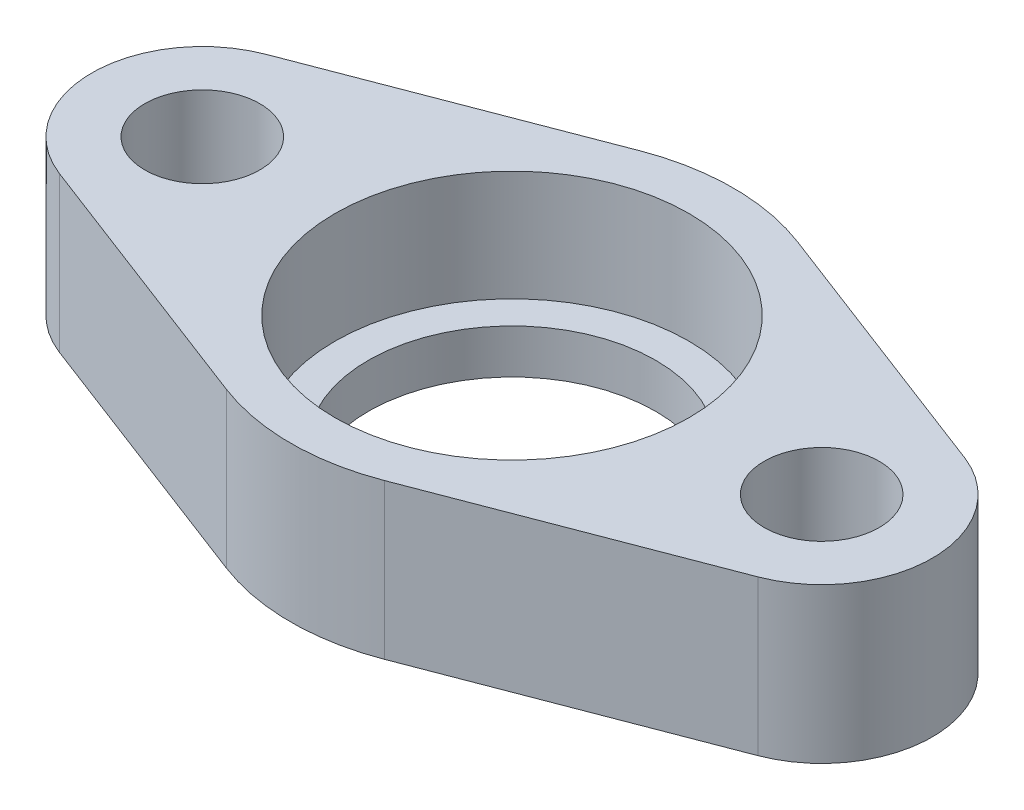
SolidWorks part; units mm, degrees
ref_plane "Front Plane" through (0, 0, 0) normal (0, 0, 1) x (1, 0, 0)
ref_plane "Top Plane" through (0, 0, 0) normal (0, 1, 0) x (1, 0, 0)
ref_plane "Right Plane" through (0, 0, 0) normal (1, 0, 0) x (0, 0, -1)
sketch "Sketch1" plane through (0, 0, 0) normal (0, 1, 0) x (1, 0, 0)
  circle A0 centre (0, 0) radius 4
  circle A1 centre (0, 0) radius 5
  dimension "D1" = 8
  dimension "D2" = 10
extrude "Boss-Extrude1" add sketch "Sketch1" along normal blind 3.5
sketch "Sketch2" plane through (0, 0, 0) normal (0, 1, 0) x (1, 0, 0)
  line L0 (-7.8929, 2.3351) -> (-1.7857, 4.6702)
  line L1 (-9.3607, 0) -> (9.6441, 0) construction
  line L2 (0, 4) -> (0, -5.1211) construction
  line L3 (-7.8929, -2.3351) -> (-1.7857, -4.6702)
  line L4 (7.8929, -2.3351) -> (1.7857, -4.6702)
  line L5 (7.8929, 2.3351) -> (1.7857, 4.6702)
  arc A0 (-7.8929, 2.3351) -> (-7.8929, -2.3351) centre (-7, 0) ccw
  arc A1 (-1.7857, 4.6702) -> (-1.7857, -4.6702) centre (0, 0) ccw
  arc A2 (7.8929, 2.3351) -> (7.8929, -2.3351) centre (7, 0) cw
  arc A3 (1.7857, -4.6702) -> (1.7857, 4.6702) centre (0, 0) ccw
  dimension "D1" = 5
  dimension "D3" = 10
  dimension "D2" = 7
extrude "Boss-Extrude2" add sketch "Sketch2" along normal up to surface (3.5 mm away) up to face at (0, 3.5, 5)
hole_wizard "M2 Clearance Hole1" positions "Sketch4" profile "Sketch3" hole size "M2" standard "ANSI Metric" end condition through all
sketch "Sketch4" plane through (0, 3.5, 0) normal (0, 1, 0) x (1, 0, 0)
  line L0 (0, 1.4124) -> (0, -1.3898) construction
  point P0 (-7, 0)
  point P9 (7, 0)
sketch "Sketch3" plane through (-7, 3.5, 0) normal (1, 0, 0) x (0, 0, 1)
  line L0 (0, 0) -> (0, 3.5)
  line L1 (0, 3.5) -> (1.3, 3.5)
  line L2 (1.3, 3.5) -> (1.3, 0)
  line L5 (1.3, 0) -> (0, 0)
  line L11 (0, -6.35) -> (0, 107.95) construction
  dimension "Thru Hole Dia." = 2.6
  dimension "Thru Hole Depth" = 3.5
sketch "Sketch6" plane through (0, 0, 0) normal (0, -1, 0) x (1, 0, 0)
  circle A0 centre (0, 0) radius 4 construction
  circle A1 centre (0, 0) radius 4
  circle A2 centre (0, 0) radius 3.25
  dimension "D1" = 6.5
extrude "Boss-Extrude4" add sketch "Sketch6" against normal blind 1
